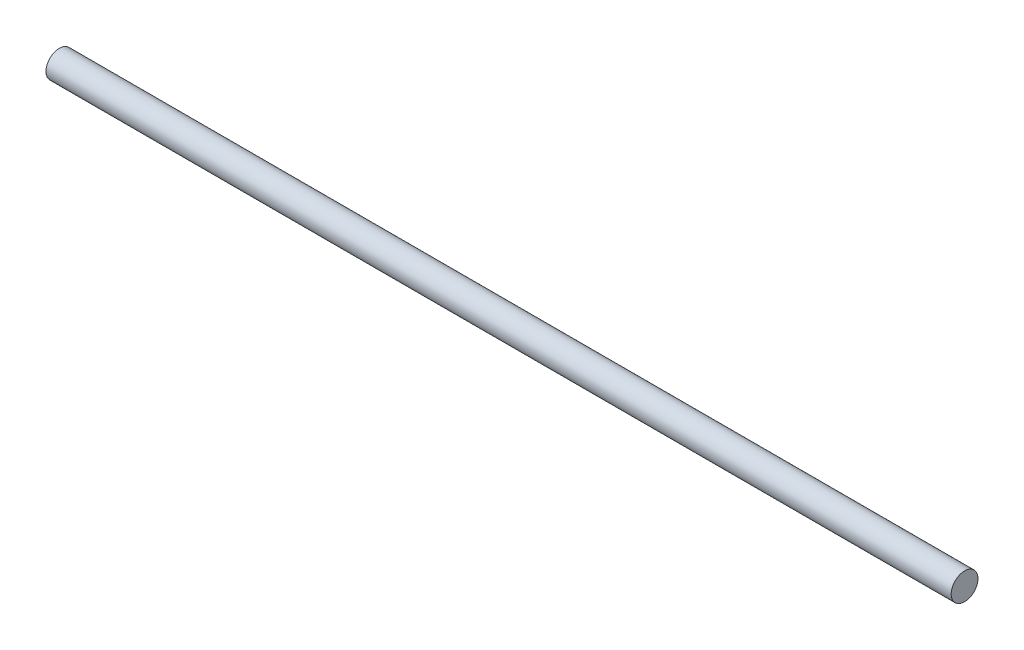
SolidWorks part; units mm, degrees
ref_plane "Front Plane" through (0, 0, 0) normal (0, 0, 1) x (1, 0, 0)
ref_plane "Top Plane" through (0, 0, 0) normal (0, 1, 0) x (1, 0, 0)
ref_plane "Right Plane" through (0, 0, 0) normal (1, 0, 0) x (0, 0, -1)
sketch "Sketch1" plane through (0, 0, 0) normal (1, 0, 0) x (0, 0, -1)
  circle A0 centre (0, 0) radius 4
  dimension "D1" = 8
extrude "Boss-Extrude1" add sketch "Sketch1" along normal blind 270
